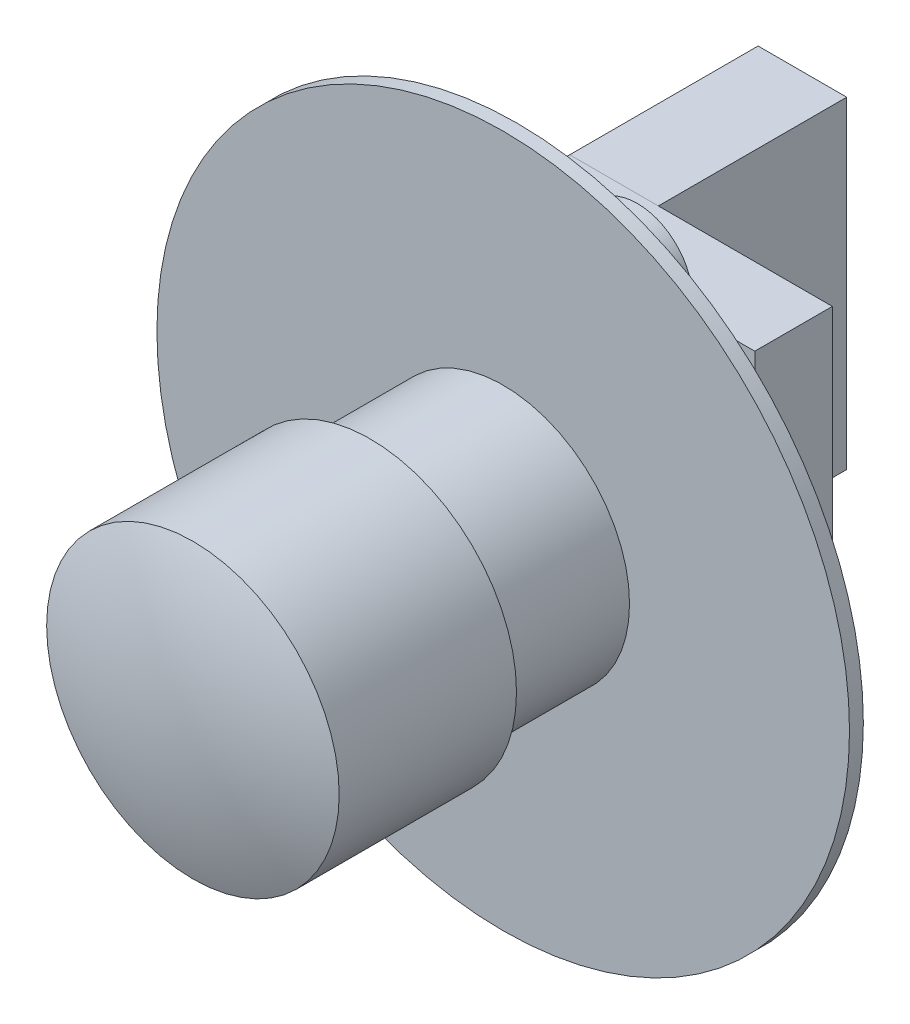
SolidWorks part; units mm, degrees
material "Rubber"
ref_plane "Front Plane" through (0, 0, 0) normal (0, 0, 1) x (1, 0, 0)
ref_plane "Top Plane" through (0, 0, 0) normal (0, 1, 0) x (1, 0, 0)
ref_plane "Right Plane" through (0, 0, 0) normal (1, 0, 0) x (0, 0, -1)
sketch "Sketch1" plane through (0, 0, 0) normal (0, 0, 1) x (1, 0, 0)
  circle A0 centre (0, 0) radius 16.764
  dimension "D1" = 33.528
extrude "Boss-Extrude1" add sketch "Sketch1" along normal blind 20.32
sketch "Sketch2" plane through (0, 0, 0) normal (0, 1, 0) x (1, 0, 0)
  line L0 (0, -17.0563) -> (0, -23.495) construction
  line L1 (0, -20.32) -> (16.764, -20.32)
  line L2 (-16.764, -20.32) -> (16.764, -20.32) construction
  line L3 (0, -20.32) -> (0, -23.495)
  arc A0 (0, -23.495) -> (16.764, -20.32) centre (0, 22.3495) ccw
  dimension "D1" = 3.175
revolve "Revolve1" add sketch "Sketch2" angle 360 about L0
sketch "Sketch3" plane through (0, 0, 0) normal (0, 0, -1) x (-1, 0, 0)
  circle A0 centre (0, 0) radius 14.478
  dimension "D1" = 28.956
extrude "Boss-Extrude2" add sketch "Sketch3" along normal blind 15.24
sketch "Sketch4" plane through (0, 0, -15.24) normal (0, 0, -1) x (-1, 0, 0)
  line L1 (-12.7, 15.875) -> (12.7, 15.875)
  line L2 (-12.7, 15.875) -> (-12.7, -15.875)
  line L3 (-12.7, -15.875) -> (12.7, -15.875)
  line L4 (12.7, 15.875) -> (12.7, -15.875)
  line L5 (-12.7, 15.875) -> (12.7, -15.875) construction
  line L6 (-12.7, -15.875) -> (12.7, 15.875) construction
  point P0 (0, 0)
  dimension "D1" = 25.4
  dimension "D2" = 31.75
extrude "Boss-Extrude3" [suppressed] add sketch "Sketch4" along normal blind 25.4
sketch "Sketch5" plane through (0, 0, -15.24) normal (0, 0, -1) x (-1, 0, 0)
  circle A0 centre (0, 0) radius 39.6875
  dimension "D1" = 79.375
extrude "Boss-Extrude4" add sketch "Sketch5" along normal blind 1.5875
sketch "Sketch6" plane through (0, 0, -16.8275) normal (0, 0, -1) x (-1, 0, 0)
  circle A0 centre (0, 0) radius 11.1125
  dimension "D1" = 22.225
extrude "Boss-Extrude5" add sketch "Sketch6" along normal blind 6.35
sketch "Sketch7" plane through (0, 0, -23.1775) normal (0, 0, -1) x (-1, 0, 0)
  circle A0 centre (0, 0) radius 14.605
  dimension "D1" = 29.21
extrude "Boss-Extrude6" add sketch "Sketch7" along normal blind 5.842
sketch "Sketch8" plane through (0, 0, -29.0195) normal (0, 0, -1) x (-1, 0, 0)
  line L1 (-15.0495, 18.4785) -> (15.0495, 18.4785)
  line L2 (-15.0495, 18.4785) -> (-15.0495, -18.4785)
  line L3 (-15.0495, -18.4785) -> (15.0495, -18.4785)
  line L4 (15.0495, 18.4785) -> (15.0495, -18.4785)
  line L5 (-15.0495, 18.4785) -> (15.0495, -18.4785) construction
  line L6 (-15.0495, -18.4785) -> (15.0495, 18.4785) construction
  point P0 (0, 0)
  dimension "D1" = 36.957
  dimension "D2" = 30.099
extrude "Boss-Extrude7" add sketch "Sketch8" along normal blind 8.89
sketch "Sketch9" plane through (0, 0, -29.0195) normal (0, 0, 1) x (1, 0, 0)
  line L0 (6.35, 18.4785) -> (-6.35, 18.4785)
  line L1 (-15.0495, 18.4785) -> (15.0495, 18.4785) construction
  arc A0 (-6.35, 18.4785) -> (6.35, 18.4785) centre (0, 18.4785) cw
  dimension "D1" = 6.35
extrude "Boss-Extrude8" add sketch "Sketch9" against normal blind 1.5875
sketch "Sketch10" plane through (0, 0, -37.9095) normal (0, 0, -1) x (-1, 0, 0)
  line L0 (-15.0495, -18.4785) -> (15.0495, -18.4785) construction
  line L1 (15.0495, 18.4785) -> (4.8895, 18.4785)
  line L2 (15.0495, 18.4785) -> (15.0495, -18.4785)
  line L3 (15.0495, -18.4785) -> (4.8895, -18.4785)
  line L4 (4.8895, 18.4785) -> (4.8895, -18.4785)
  dimension "D1" = 10.16
extrude "Boss-Extrude9" add sketch "Sketch10" along normal blind 21.59 separate body
